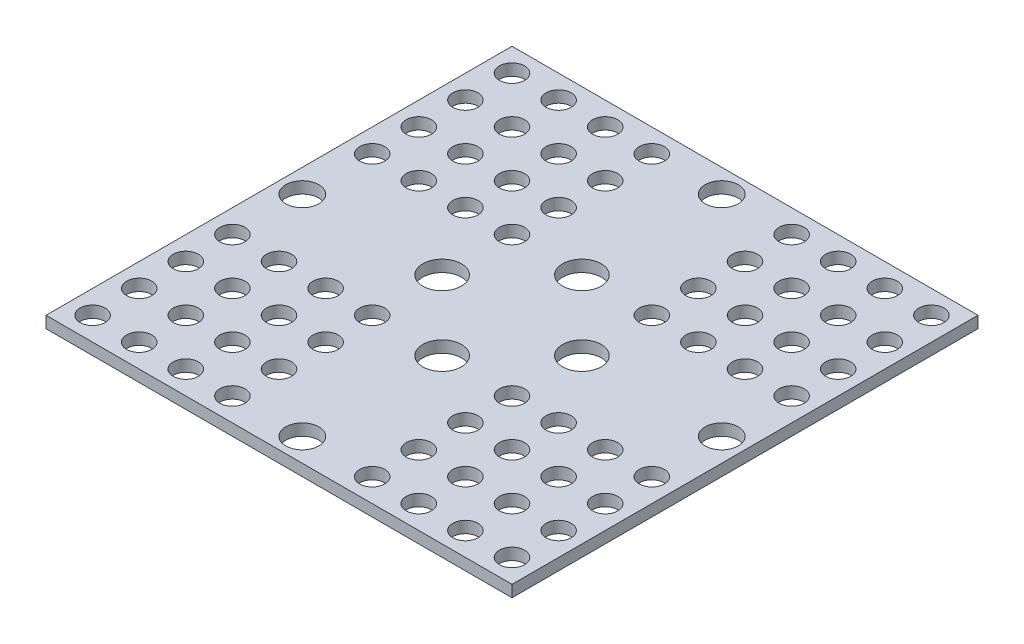
SolidWorks part; units mm, degrees
ref_plane "Front Plane" through (0, 0, 0) normal (0, 0, 1) x (1, 0, 0)
ref_plane "Top Plane" through (0, 0, 0) normal (0, 1, 0) x (1, 0, 0)
ref_plane "Right Plane" through (0, 0, 0) normal (1, 0, 0) x (0, 0, -1)
sketch "Sketch1" plane through (0, 0, 0) normal (0, 1, 0) x (1, 0, 0)
  line L1 (-63.5, -63.5) -> (63.5, -63.5)
  line L2 (-63.5, -63.5) -> (-63.5, 63.5)
  line L3 (-63.5, 63.5) -> (63.5, 63.5)
  line L4 (63.5, -63.5) -> (63.5, 63.5)
  line L5 (-63.5, -63.5) -> (63.5, 63.5) construction
  line L6 (-63.5, 63.5) -> (63.5, -63.5) construction
  circle A0 centre (0, 19.05) radius 5.2728
  circle A1 centre (0, 57.15) radius 4.5103
  circle A2 centre (57.15, 0) radius 4.5103
  circle A3 centre (19.05, 0) radius 5.2728
  circle A4 centre (0, -19.05) radius 5.2728
  circle A5 centre (0, -57.15) radius 4.5103
  circle A6 centre (-57.15, 0) radius 4.5103
  circle A7 centre (-19.05, 0) radius 5.2728
  circle A8 centre (-57.15, 57.15) radius 3.429
  circle A9 centre (-44.45, 57.15) radius 3.429
  circle A10 centre (-31.75, 57.15) radius 3.429
  circle A11 centre (-19.05, 57.15) radius 3.429
  circle A14 centre (19.05, 57.15) radius 3.429
  circle A15 centre (31.75, 57.15) radius 3.429
  circle A16 centre (44.45, 57.15) radius 3.429
  circle A17 centre (57.15, 57.15) radius 3.429
  circle A18 centre (-44.45, 44.45) radius 3.429
  circle A19 centre (-31.75, 44.45) radius 3.429
  circle A20 centre (-19.05, 44.45) radius 3.429
  circle A23 centre (19.05, 44.45) radius 3.429
  circle A24 centre (31.75, 44.45) radius 3.429
  circle A25 centre (44.45, 44.45) radius 3.429
  circle A26 centre (57.15, 44.45) radius 3.429
  circle A27 centre (-44.45, 31.75) radius 3.429
  circle A28 centre (-31.75, 31.75) radius 3.429
  circle A29 centre (-19.05, 31.75) radius 3.429
  circle A32 centre (19.05, 31.75) radius 3.429
  circle A33 centre (31.75, 31.75) radius 3.429
  circle A34 centre (44.45, 31.75) radius 3.429
  circle A35 centre (57.15, 31.75) radius 3.429
  circle A36 centre (-44.45, 19.05) radius 3.429
  circle A37 centre (-31.75, 19.05) radius 3.429
  circle A38 centre (-19.05, 19.05) radius 3.429
  circle A41 centre (19.05, 19.05) radius 3.429
  circle A42 centre (31.75, 19.05) radius 3.429
  circle A43 centre (44.45, 19.05) radius 3.429
  circle A44 centre (57.15, 19.05) radius 3.429
  circle A63 centre (-44.45, -19.05) radius 3.429
  circle A64 centre (-31.75, -19.05) radius 3.429
  circle A65 centre (-19.05, -19.05) radius 3.429
  circle A68 centre (19.05, -19.05) radius 3.429
  circle A69 centre (31.75, -19.05) radius 3.429
  circle A70 centre (44.45, -19.05) radius 3.429
  circle A71 centre (57.15, -19.05) radius 3.429
  circle A72 centre (-44.45, -31.75) radius 3.429
  circle A73 centre (-31.75, -31.75) radius 3.429
  circle A74 centre (-19.05, -31.75) radius 3.429
  circle A77 centre (19.05, -31.75) radius 3.429
  circle A78 centre (31.75, -31.75) radius 3.429
  circle A79 centre (44.45, -31.75) radius 3.429
  circle A80 centre (57.15, -31.75) radius 3.429
  circle A81 centre (-44.45, -44.45) radius 3.429
  circle A82 centre (-31.75, -44.45) radius 3.429
  circle A83 centre (-19.05, -44.45) radius 3.429
  circle A86 centre (19.05, -44.45) radius 3.429
  circle A87 centre (31.75, -44.45) radius 3.429
  circle A88 centre (44.45, -44.45) radius 3.429
  circle A89 centre (57.15, -44.45) radius 3.429
  circle A90 centre (-44.45, -57.15) radius 3.429
  circle A91 centre (-31.75, -57.15) radius 3.429
  circle A92 centre (-19.05, -57.15) radius 3.429
  circle A95 centre (19.05, -57.15) radius 3.429
  circle A96 centre (31.75, -57.15) radius 3.429
  circle A97 centre (44.45, -57.15) radius 3.429
  circle A98 centre (57.15, -57.15) radius 3.429
  circle A99 centre (-57.15, 44.45) radius 3.429
  circle A100 centre (-57.15, 31.75) radius 3.429
  circle A101 centre (-57.15, 19.05) radius 3.429
  circle A104 centre (-57.15, -19.05) radius 3.429
  circle A105 centre (-57.15, -31.75) radius 3.429
  circle A106 centre (-57.15, -44.45) radius 3.429
  circle A107 centre (-57.15, -57.15) radius 3.429
  circle A108 centre (-57.15, 6.35) radius 3.429 [skipped]
  circle A109 centre (-57.15, -6.35) radius 3.429 [skipped]
  circle A110 centre (-44.45, -6.35) radius 3.429 [skipped]
  circle A111 centre (-44.45, 6.35) radius 3.429 [skipped]
  circle A112 centre (-31.75, -6.35) radius 3.429 [skipped]
  circle A113 centre (-31.75, 6.35) radius 3.429 [skipped]
  circle A114 centre (-19.05, 6.35) radius 3.429 [skipped]
  circle A115 centre (-19.05, -6.35) radius 3.429 [skipped]
  circle A116 centre (-6.35, 6.35) radius 3.429 [skipped]
  circle A117 centre (-6.35, -6.35) radius 3.429 [skipped]
  circle A118 centre (-6.35, -19.05) radius 3.429 [skipped]
  circle A119 centre (-6.35, -31.75) radius 3.429 [skipped]
  circle A120 centre (-6.35, -44.45) radius 3.429 [skipped]
  circle A121 centre (-6.35, -57.15) radius 3.429 [skipped]
  circle A122 centre (6.35, -57.15) radius 3.429 [skipped]
  circle A123 centre (6.35, -44.45) radius 3.429 [skipped]
  circle A124 centre (6.35, -31.75) radius 3.429 [skipped]
  circle A125 centre (6.35, -19.05) radius 3.429 [skipped]
  circle A126 centre (6.35, -6.35) radius 3.429 [skipped]
  circle A127 centre (19.05, -6.35) radius 3.429 [skipped]
  circle A128 centre (31.75, -6.35) radius 3.429 [skipped]
  circle A129 centre (44.45, -6.35) radius 3.429 [skipped]
  circle A130 centre (57.15, -6.35) radius 3.429 [skipped]
  circle A131 centre (57.15, 6.35) radius 3.429 [skipped]
  circle A132 centre (44.45, 6.35) radius 3.429 [skipped]
  circle A133 centre (31.75, 6.35) radius 3.429 [skipped]
  circle A134 centre (19.05, 6.35) radius 3.429 [skipped]
  circle A135 centre (6.35, 6.35) radius 3.429 [skipped]
  circle A136 centre (6.35, 19.05) radius 3.429 [skipped]
  circle A137 centre (6.35, 31.75) radius 3.429 [skipped]
  circle A138 centre (6.35, 44.45) radius 3.429 [skipped]
  circle A139 centre (6.35, 57.15) radius 3.429 [skipped]
  circle A140 centre (-6.35, 57.15) radius 3.429 [skipped]
  circle A141 centre (-6.35, 44.45) radius 3.429 [skipped]
  circle A142 centre (-6.35, 31.75) radius 3.429 [skipped]
  circle A143 centre (-6.35, 19.05) radius 3.429 [skipped]
  point P0 (0, 0)
  point P24 (0, 0)
  dimension "D3" = 19.05
  dimension "D4" = 38.1
  dimension "D5" = 6.858
  dimension "D1" = 127
  dimension "D2" = 127
  dimension "D6" = 6.35
  dimension "D7" = 6.35
  dimension "D8" = 10
  dimension "D9" = 10
extrude "Boss-Extrude1" add sketch "Sketch1" along normal blind 3.175
